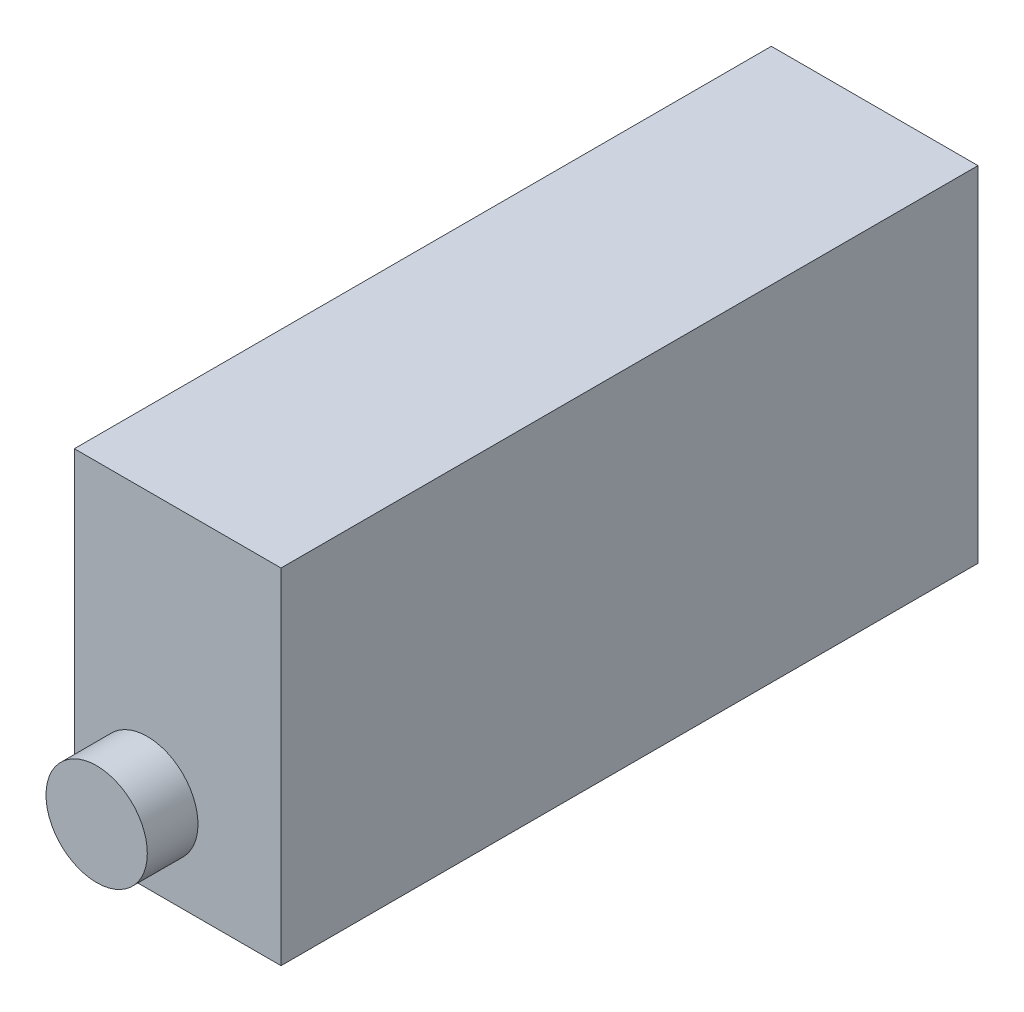
SolidWorks part; units mm, degrees
ref_plane "Front" through (0, 0, 0) normal (0, 0, 1) x (1, 0, 0)
ref_plane "Top" through (0, 0, 0) normal (0, 1, 0) x (1, 0, 0)
ref_plane "Right" through (0, 0, 0) normal (1, 0, 0) x (0, 0, -1)
sketch "Sketch1" plane through (0, 0, 0) normal (0, 0, 1) x (1, 0, 0)
  line L1 (25.5, 42.5) -> (-25.5, 42.5)
  line L2 (25.5, 42.5) -> (25.5, -42.5)
  line L3 (25.5, -42.5) -> (-25.5, -42.5)
  line L4 (-25.5, 42.5) -> (-25.5, -42.5)
  line L5 (0, -42.5) -> (0, 42.5) construction
  line L6 (25.5, 0) -> (-25.5, 0) construction
  point P0 (0, 0)
  dimension "D1" = 51
  dimension "D2" = 85
extrude "Boss-Extrude1" add sketch "Sketch1" against normal blind 172
sketch "Sketch3" plane through (0, 0, 0) normal (0, 0, 1) x (1, 0, 0)
  line L0 (-25.5, -42.5) -> (25.5, -42.5) construction
  line L1 (-25.5, 42.5) -> (-25.5, -42.5) construction
  circle A0 centre (-7.5, -22.5) radius 12.5
  point P2 (0, 0)
  dimension "D1" = 25
  dimension "D2" = 20
  dimension "D3" = 18
extrude "Boss-Extrude2" add sketch "Sketch3" along normal blind 12.5
